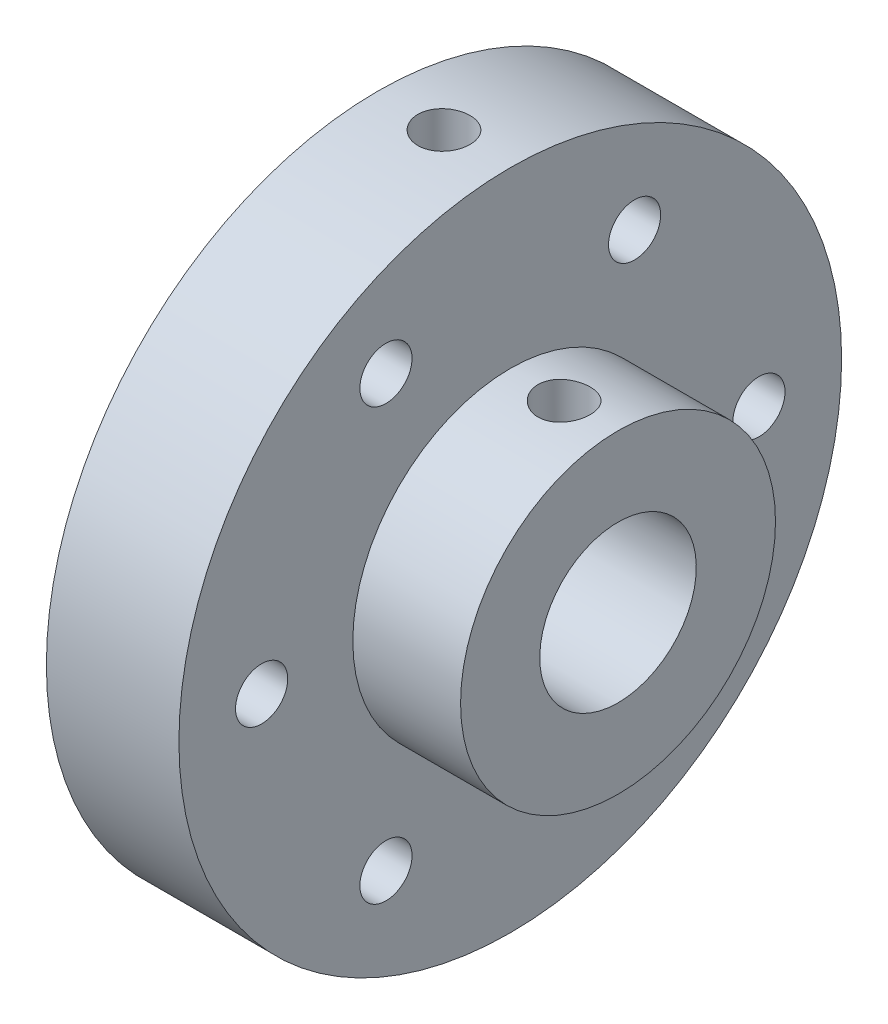
SolidWorks part; units mm, degrees
ref_plane "Plan de face" through (0, 0, 0) normal (0, 0, 1) x (1, 0, 0)
ref_plane "Plan de dessus" through (0, 0, 0) normal (0, 1, 0) x (1, 0, 0)
ref_plane "Plan de droite" through (0, 0, 0) normal (1, 0, 0) x (0, 0, -1)
sketch "Esquisse1" plane through (0, 0, 0) normal (0, 0, 1) x (1, 0, 0)
  line L0 (0, 0) -> (0, 12.7)
  line L1 (0, 12.7) -> (5.08, 12.7)
  line L2 (5.08, 12.7) -> (5.08, 6.035)
  line L3 (5.08, 6.035) -> (9.21, 6.035)
  line L4 (9.21, 6.035) -> (9.21, 0)
  line L5 (9.21, 0) -> (0, 0)
revolve "Révolution1" add sketch "Esquisse1" angle 360 about L5
sketch "Esquisse2" plane through (0, 0, 0) normal (-1, 0, 0) x (0, 0, 1)
  circle A0 centre (9.53, 0) radius 1
  circle A1 centre (4.765, -8.2532) radius 1
  circle A2 centre (-4.765, -8.2532) radius 1
  circle A3 centre (-9.53, 0) radius 1
  circle A4 centre (-4.765, 8.2532) radius 1
  circle A5 centre (4.765, 8.2532) radius 1
  circle A6 centre (0, 0) radius 3
  dimension "D2" = 6
  dimension "D1" = 9.53
extrude "Enlèv. mat.-Extru.1" cut sketch "Esquisse2" against normal through all
sketch "Esquisse4" plane through (0, 0, 0) normal (0, 1, 0) x (1, 0, 0)
  line L0 (0, 0) -> (5.08, 0) construction
  line L1 (0, 12.7) -> (0, -12.7) construction
  line L2 (5.08, -6.035) -> (5.08, 6.035) construction
  line L3 (5.08, 0) -> (9.21, 0) construction
  line L4 (9.21, -6.035) -> (9.21, 6.035) construction
  circle A0 centre (2.54, 0) radius 1
  circle A1 centre (7.145, 0) radius 1
extrude "Enlèv. mat.-Extru.2" cut sketch "Esquisse4" along normal through all
